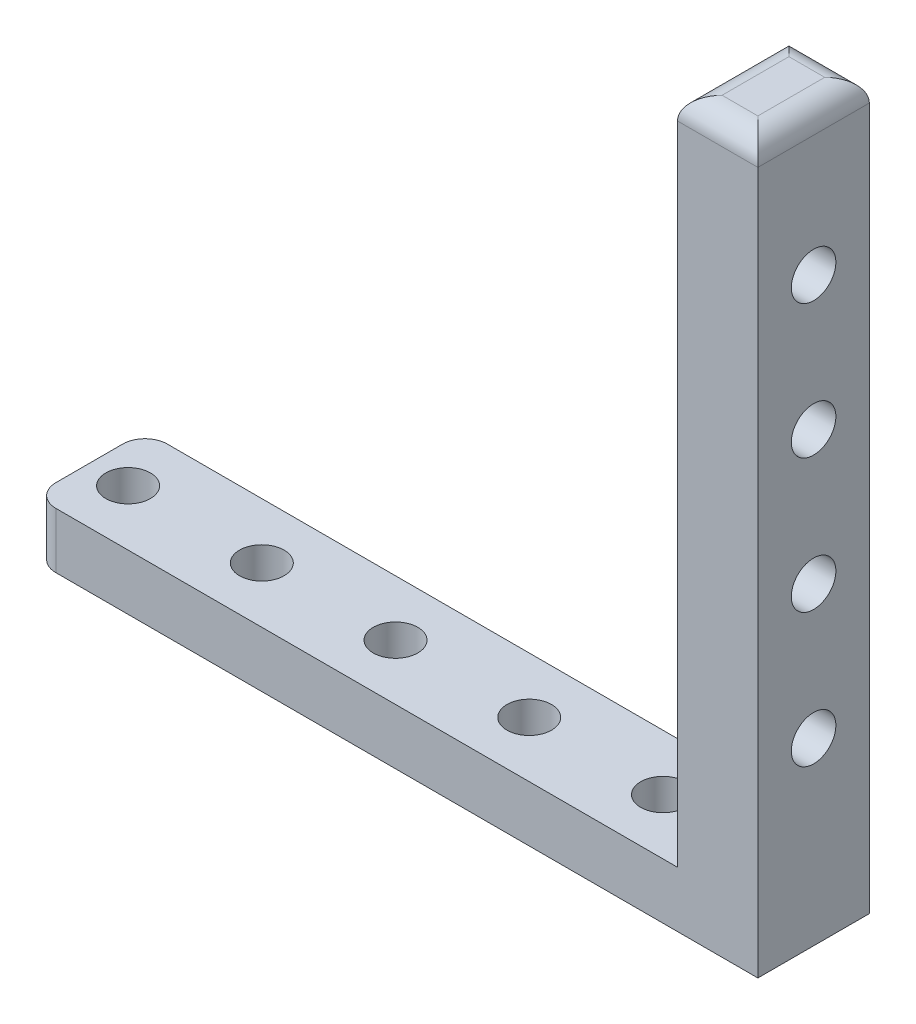
SolidWorks part; units mm, degrees
ref_plane "Front Plane" through (0, 0, 0) normal (0, 0, 1) x (1, 0, 0)
ref_plane "Top Plane" through (0, 0, 0) normal (0, 1, 0) x (1, 0, 0)
ref_plane "Right Plane" through (0, 0, 0) normal (1, 0, 0) x (0, 0, -1)
sketch "Sketch2" plane through (0, 0, 0) normal (0, 1, 0) x (1, 0, 0)
  line L1 (-37.8571, 5.8036) -> (27.1429, 5.8036)
  line L2 (-37.8571, 5.8036) -> (-37.8571, -4.1964)
  line L3 (-37.8571, -4.1964) -> (27.1429, -4.1964)
  line L4 (27.1429, 5.8036) -> (27.1429, -4.1964)
  dimension "D1" = 65
  dimension "D2" = 10
extrude "Boss-Extrude1" add sketch "Sketch2" along normal blind 5
fillet "Fillet1" radius 2 1 edges at (-37.8571, 2.5, 4.1964)
fillet "Fillet2" radius 2 1 edges at (-37.8571, 2.5, -5.8036)
sketch "Sketch3" plane through (0, 5, 0) normal (0, 1, 0) x (1, 0, 0)
  line L0 (27.1429, 5.8036) -> (-35.8571, 5.8036) construction
  line L1 (-35.8571, -4.1964) -> (27.1429, -4.1964) construction
  circle A0 centre (13.6251, 0.8036) radius 2
  point P2 (13.6251, 0.6985)
  point P7 (15.4463, -4.1964)
  dimension "D1" = 4
  dimension "D2" = 10
extrude "Cut-Extrude1" cut sketch "Sketch3" against normal blind 15
pattern_linear "LPattern1" count 5 spacing 12 along (-1, 0, 0) of "Cut-Extrude1"
sketch "Sketch4" plane through (0, 5, 0) normal (0, 1, 0) x (1, 0, 0)
  line L0 (-35.8571, -4.1964) -> (27.1429, -4.1964) construction
  line L1 (27.1429, 5.8036) -> (19.9292, 5.8036)
  line L2 (27.1429, 5.8036) -> (27.1429, -4.1964)
  line L3 (27.1429, -4.1964) -> (19.9292, -4.1964)
  line L4 (19.9292, 5.8036) -> (19.9292, -4.1964)
extrude "Boss-Extrude2" add sketch "Sketch4" along normal blind 60
sketch "Sketch5" plane through (19.9292, 0, 0) normal (-1, 0, 0) x (0, 0, 1)
  line L0 (-0.8036, 5) -> (-0.8036, 26.14)
  line L1 (-3.8036, 5) -> (2.1964, 5) construction
  line L2 (-0.8036, 26.14) -> (-0.8036, 28.14)
  circle A0 centre (-0.8036, 28.14) radius 2
  dimension "D1" = 21.14
  dimension "D2" = 2
extrude "Cut-Extrude2" cut sketch "Sketch5" against normal blind 60
pattern_linear "LPattern2" count 3 spacing 12 along (0, 1, 0) count 2 spacing 12 along (0, -1, 0) of "Cut-Extrude2"
fillet "Fillet3" radius 2 4 edges at (27.1429, 65, -0.8036) (19.9292, 65, -0.8036) (23.536, 65, -5.8036) (23.536, 65, 4.1964)
